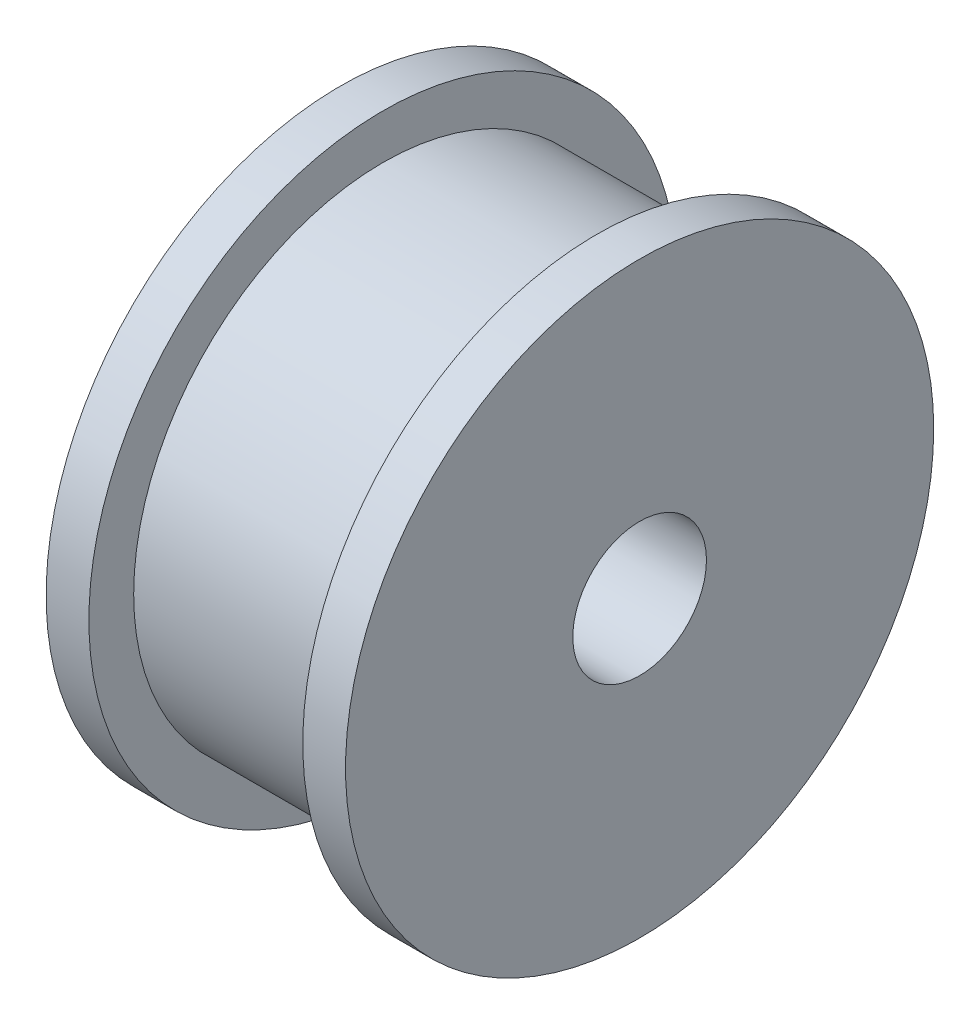
SolidWorks part; units mm, degrees
material "6061-T6 (SS)"
ref_plane "Front Plane" through (0, 0, 0) normal (0, 0, 1) x (1, 0, 0)
ref_plane "Top Plane" through (0, 0, 0) normal (0, 1, 0) x (1, 0, 0)
ref_plane "Right Plane" through (0, 0, 0) normal (1, 0, 0) x (0, 0, -1)
sketch "Sketch1" plane through (0, 0, 0) normal (0, 0, 1) x (1, 0, 0)
  line L1 (-5.6, 11) -> (-4, 11)
  line L2 (-4, 11) -> (-4, 9.325)
  line L3 (-4, 9.325) -> (4, 9.325)
  line L4 (4, 9.325) -> (4, 11)
  line L5 (4, 11) -> (5.6, 11)
  line L6 (5.6, 11) -> (5.6, 2.5)
  line L7 (5.6, 2.5) -> (-5.6, 2.5)
  line L8 (0, 0) -> (-7.6744, 0) construction
  line L9 (-5.6, 11) -> (-5.6, 2.5)
  line L11 (0, 9.325) -> (0, 2.5) construction
  dimension "D1" = 5
  dimension "D2" = 22
  dimension "D3" = 18.65
  dimension "D4" = 8
  dimension "D6" = 1.6
revolve "Revolve1" add sketch "Sketch1" angle 360 about L8
